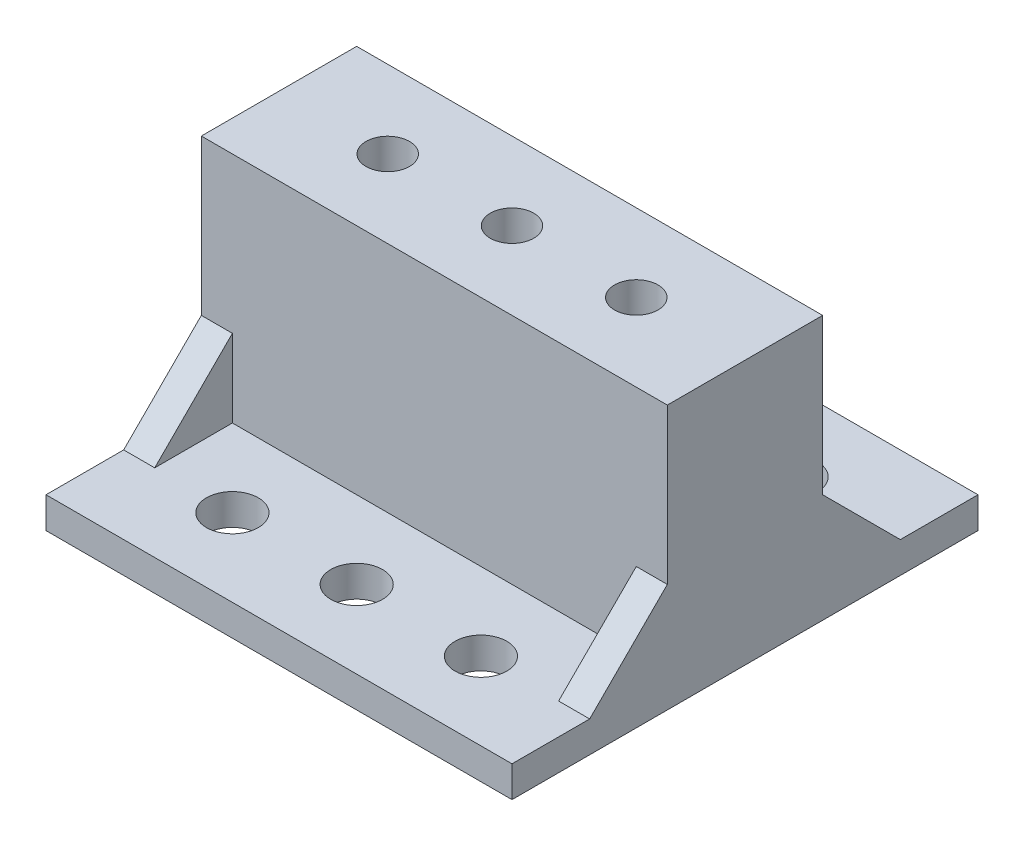
SolidWorks part; units mm, degrees
ref_plane "Alzado" through (0, 0, 0) normal (0, 0, 1) x (1, 0, 0)
ref_plane "Planta" through (0, 0, 0) normal (0, 1, 0) x (1, 0, 0)
ref_plane "Vista lateral" through (0, 0, 0) normal (1, 0, 0) x (0, 0, -1)
sketch "Croquis1" plane through (0, 0, 0) normal (0, 1, 0) x (1, 0, 0)
  line L5 (-22.5, 22.5) -> (22.5, 22.5)
  line L6 (-22.5, 22.5) -> (-22.5, -22.5)
  line L7 (-22.5, -22.5) -> (22.5, -22.5)
  line L8 (22.5, 22.5) -> (22.5, -22.5)
  line L9 (-22.5, 22.5) -> (22.5, -22.5) construction
  line L10 (-22.5, -22.5) -> (22.5, 22.5) construction
  point P0 (0, 0)
  dimension "D1" = 45
  dimension "D2" = 45
extrude "Saliente-Extruir1" add sketch "Croquis1" along normal blind 3
sketch "Croquis2" plane through (0, 3, 0) normal (0, 1, 0) x (1, 0, 0)
  line L6 (-22.5, 22.5) -> (-22.5, -22.5) construction
  line L7 (22.5, 7.5) -> (-22.5, 7.5)
  line L10 (22.5, 7.5) -> (22.5, -7.5)
  line L11 (22.5, -7.5) -> (-22.5, -7.5)
  line L12 (-22.5, 7.5) -> (-22.5, -7.5)
  line L13 (22.5, 7.5) -> (-22.5, -7.5) construction
  line L14 (22.5, -7.5) -> (-22.5, 7.5) construction
  line L15 (22.5, 22.5) -> (-22.5, 22.5) construction
  point P0 (0, 0)
  dimension "D1" = 15
extrude "Saliente-Extruir2" add sketch "Croquis2" along normal blind 22.5
sketch "Croquis3" plane through (-22.5, 0, 0) normal (-1, 0, 0) x (0, 0, 1)
  line L3 (7.5, 3) -> (15, 3)
  line L4 (7.5, 3) -> (22.5, 3) construction
  line L5 (15, 3) -> (7.5, 10.5)
  line L6 (7.5, 25.5) -> (7.5, 3) construction
  line L7 (7.5, 10.5) -> (7.5, 3)
  dimension "D1" = 45
  dimension "D2" = 7.5
extrude "Saliente-Extruir3" add sketch "Croquis3" against normal blind 3
mirror "Simetría1" about plane through (0, 0, 0) normal (1, 0, 0) of "Saliente-Extruir3"
mirror "Simetría2" about plane through (0, 0, 0) normal (0, 0, 1) of "Simetría1", "Saliente-Extruir3"
sketch "Croquis4" plane through (0, 3, 0) normal (0, 1, 0) x (1, 0, 0)
  line L0 (0, -15) -> (-12, -15) construction
  line L1 (0, -15) -> (12, -15) construction
  line L2 (0, -15) -> (0, 0) construction
  line L3 (0, -15) -> (0, -22.5) construction
  line L4 (-22.5, -22.5) -> (22.5, -22.5) construction
  line L5 (12, -15) -> (12, -7.5) construction
  line L6 (-19.5, -7.5) -> (19.5, -7.5) construction
  circle A0 centre (0, -15) radius 2.5
  circle A1 centre (-12, -15) radius 2.5
  circle A2 centre (12, -15) radius 2.5
  dimension "D1" = 5
  dimension "D2" = 12
extrude "Cortar-Extruir1" cut sketch "Croquis4" against normal blind 3
mirror "Simetría3" about plane through (0, 0, 0) normal (0, 0, 1) of "Cortar-Extruir1"
sketch "Croquis5" plane through (0, 25.5, 0) normal (0, 1, 0) x (1, 0, 0)
  line L0 (0, 0) -> (-12, 0) construction
  line L1 (0, 0) -> (12, 0) construction
  circle A0 centre (0, 0) radius 2.5
  circle A1 centre (-12, 0) radius 2.5
  circle A2 centre (12, 0) radius 2.5
  dimension "D2" = 5
  dimension "D1" = 12
hole_wizard "Taladro roscado M51" positions "Croquis6" profile "Croquis7" tap size "M5" standard "ISO"
sketch "Croquis6" plane through (0, 25.5, 0) normal (0, 1, 0) x (1, 0, 0)
  point P0 (0, 0)
  point P3 (12, 0)
  point P6 (-12, 0)
sketch "Croquis7" plane through (0, 25.5, 0) normal (1, 0, 0) x (0, 0, 1)
  line L0 (0, 0) -> (0, 19.2618)
  line L1 (0, 19.2618) -> (2.1, 18)
  line L2 (2.1, 18) -> (2.1, 0)
  line L5 (2.1, 0) -> (0, 0)
  line L10 (0, 19.2618) -> (-2.1, 18) construction
  line L11 (0, -6.35) -> (0, 107.95) construction
  dimension "Diámetro de perforador para roscar" = 4.2
  dimension "Profundidad de perforador para roscar" = 18
  dimension "Ángulo de perforador" = 118
